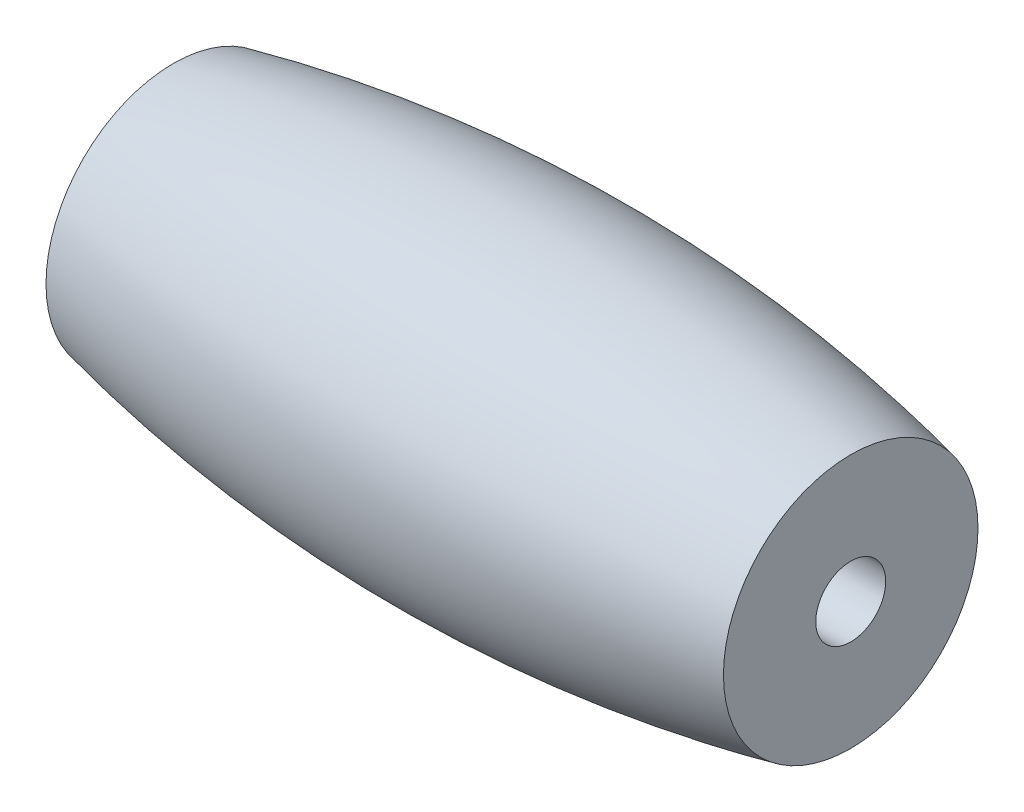
SolidWorks part; units mm, degrees
ref_plane "Front Plane" through (0, 0, 0) normal (0, 0, 1) x (1, 0, 0)
ref_plane "Top Plane" through (0, 0, 0) normal (0, 1, 0) x (1, 0, 0)
ref_plane "Right Plane" through (0, 0, 0) normal (1, 0, 0) x (0, 0, -1)
sketch "Profile" plane through (0, 0, 0) normal (0, 0, 1) x (1, 0, 0)
  line L0 (-31, 0) -> (31, 0) construction
  line L1 (-15.5, 1.6) -> (15.5, 1.6)
  line L2 (15.5, 1.6) -> (15.5, 5.8237)
  line L3 (-15.5, 5.8237) -> (-15.5, 1.6)
  arc A0 (15.5, 5.8237) -> (-15.5, 5.8237) centre (0, -65) ccw
  dimension "ArcRadius" = 72.5
  dimension "Length" = 31
  dimension "ArcCentreDrop" = 65
  dimension "BoreRadius" = 1.6
revolve "Roller" add sketch "Profile" angle 360 about L0
